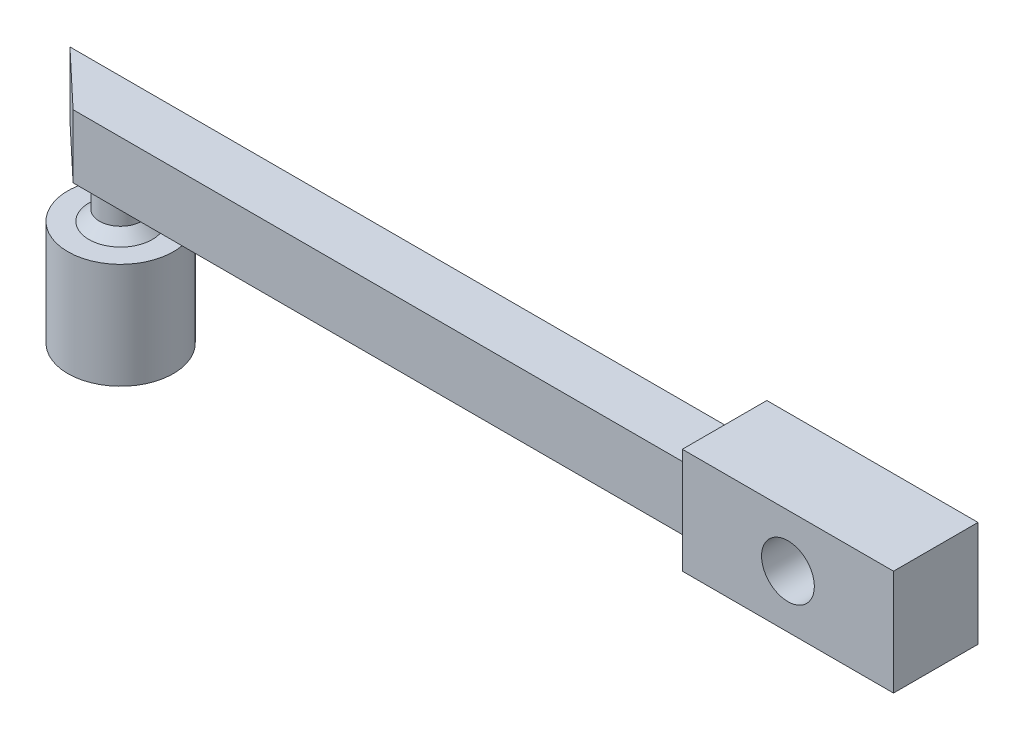
SolidWorks part; units mm, degrees
ref_plane "Piano frontale" through (0, 0, 0) normal (0, 0, 1) x (1, 0, 0)
ref_plane "Piano superiore" through (0, 0, 0) normal (0, 1, 0) x (1, 0, 0)
ref_plane "Piano destro" through (0, 0, 0) normal (1, 0, 0) x (0, 0, -1)
sketch "Schizzo1" plane through (0, 0, 0) normal (0, 0, 1) x (1, 0, 0)
  line L1 (16.5, -1.5) -> (-16.5, -1.5)
  line L2 (16.5, -1.5) -> (16.5, 1.5)
  line L3 (16.5, 1.5) -> (-16.5, 1.5)
  line L4 (-16.5, -1.5) -> (-16.5, 1.5)
  line L5 (16.5, -1.5) -> (-16.5, 1.5) construction
  line L6 (16.5, 1.5) -> (-16.5, -1.5) construction
  point P0 (0, 0)
  dimension "D1" = 3
  dimension "D2" = 33
extrude "Estrusione-Estrusione1" add sketch "Schizzo1" along normal blind 2.5
sketch "Schizzo2" plane through (0, -1.5, 0) normal (0, -1, 0) x (1, 0, 0)
  line L0 (-16.5, 0) -> (-13.85, 2.5)
  line L1 (-16.5, 2.5) -> (16.5, 2.5) construction
  line L2 (-13.85, 2.5) -> (-16.5, 2.5)
  line L3 (-16.5, 2.5) -> (-16.5, 0) construction
  line L4 (-16.5, 2.5) -> (-16.5, 0)
  dimension "D1" = 2.65
extrude "Taglio-Estrusione1" cut sketch "Schizzo2" against normal through all
sketch "Schizzo3" plane through (0, -1.5, 0) normal (0, -1, 0) x (1, 0, 0)
  line L0 (-13.85, 2.5) -> (-13.85, 0) construction
  line L1 (-16.5, 0) -> (16.5, 0) construction
  line L2 (-13.85, 1.25) -> (-12.85, 1.25) construction
  circle A0 centre (-12.85, 1.25) radius 1
  dimension "D1" = 2
  dimension "D2" = 1
extrude "Estrusione-Estrusione2" add sketch "Schizzo3" along normal blind 1.7
sketch "Schizzo5" plane through (0, -3.2, 0) normal (0, -1, 0) x (1, 0, 0)
  circle A0 centre (-12.85, 1.25) radius 2.5
  dimension "D1" = 5
extrude "Estrusione-Estrusione3" add sketch "Schizzo5" along normal blind 5
chamfer "Smusso2" distance 0.5 angle 45 1 edges at (-11.85, -3.2, 1.25)
sketch "Schizzo8" plane through (16.5, 0, 0) normal (1, 0, 0) x (0, 0, -1)
  line L0 (-2.5, -1.5) -> (0, -1.5) construction
  line L1 (-4, -1.5) -> (0, -1.5)
  line L2 (-4, -1.5) -> (-4, 3.5)
  line L3 (-4, 3.5) -> (0, 3.5)
  line L4 (0, -1.5) -> (0, 3.5)
  line L5 (-4, -1.5) -> (0, 3.5) construction
  line L6 (-4, 3.5) -> (0, -1.5) construction
  line L7 (0, -1.5) -> (0, 1.5) construction
  point P0 (-2, 1)
  dimension "D1" = 4
  dimension "D2" = 5
extrude "Estrusione-Estrusione6" add sketch "Schizzo8" along normal blind 10
sketch "Schizzo9" plane through (0, 0, 4) normal (0, 0, 1) x (1, 0, 0)
  line L0 (16.5, 3.5) -> (26.5, -1.5)
  circle A0 centre (21.5, 1) radius 1.25
  dimension "D1" = 2.5
extrude "Taglio-Estrusione3" cut sketch "Schizzo9" against normal through all contours L0 A0 | L0 A0
sketch "Schizzo10" plane through (0, -8.2, 0) normal (0, -1, 0) x (1, 0, 0)
  line L0 (-14.35, -0.75) -> (-11.35, -0.75)
  line L1 (-16.5, 0) -> (26.5, 0) construction
  circle A1 centre (-12.85, 1.25) radius 2.5
  circle A2 centre (-12.85, 1.25) radius 2.5
  point P7 (-12.85, -1.25)
  circle M3 centre (-12.85, 1.25) radius 2.5
  dimension "D2" = 0.5
  dimension "D1" = 0
extrude "Taglio-Estrusione4" cut sketch "Schizzo10" against normal up to surface (5 mm away) contours L0 M3
